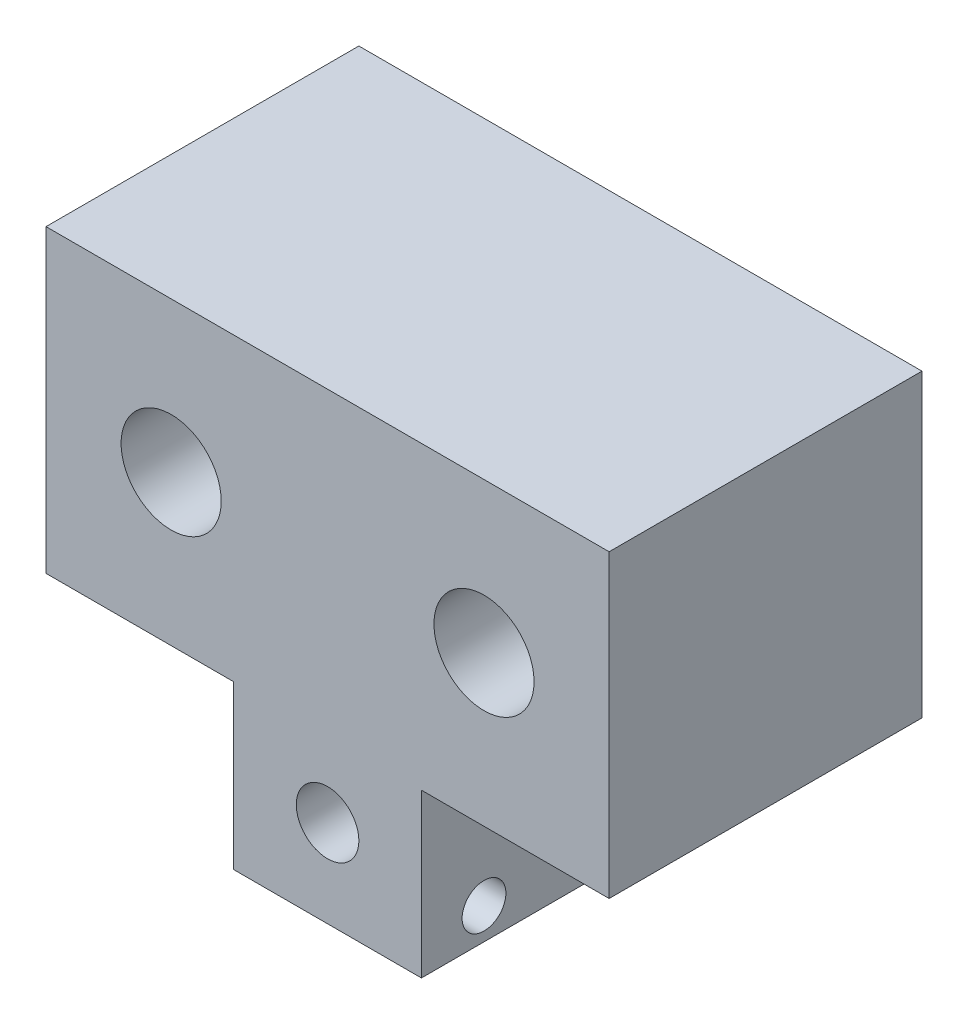
SolidWorks part; units mm, degrees
ref_plane "Plan de face" through (0, 0, 0) normal (0, 0, 1) x (1, 0, 0)
ref_plane "Plan de dessus" through (0, 0, 0) normal (0, 1, 0) x (1, 0, 0)
ref_plane "Plan de droite" through (0, 0, 0) normal (1, 0, 0) x (0, 0, -1)
sketch "Esquisse1" plane through (0, 0, 0) normal (0, 0, 1) x (1, 0, 0)
  line L1 (-18.3024, 11.783) -> (26.6976, 11.783)
  line L2 (-18.3024, 11.783) -> (-18.3024, -12.217)
  line L3 (-18.3024, -12.217) -> (26.6976, -12.217)
  line L4 (26.6976, 11.783) -> (26.6976, -12.217)
  circle A0 centre (-8.3024, -0.217) radius 4
  circle A1 centre (16.6976, -0.217) radius 4
  dimension "D3" = 8
  dimension "D4" = 8
  dimension "D5" = 12
  dimension "D6" = 10
  dimension "D7" = 12
  dimension "D8" = 12
  dimension "D9" = 10
  dimension "D1" = 45
  dimension "D2" = 24
extrude "Boss.-Extru.1" add sketch "Esquisse1" along normal blind 25
sketch "Esquisse2" plane through (0, 0, 25) normal (0, 0, 1) x (1, 0, 0)
  line L0 (-18.3024, -12.217) -> (26.6976, -12.217) construction
  line L1 (-3.3024, -25.217) -> (11.6976, -25.217)
  line L2 (-3.3024, -25.217) -> (-3.3024, -12.217)
  line L3 (-3.3024, -12.217) -> (11.6976, -12.217)
  line L4 (11.6976, -25.217) -> (11.6976, -12.217)
  line L7 (-18.3024, 11.783) -> (-18.3024, -12.217) construction
  circle A0 centre (4.1976, -18.217) radius 2.5
  dimension "D4" = 5
  dimension "D6" = 7.5
  dimension "D1" = 13
  dimension "D2" = 15
  dimension "D3" = 15
  dimension "D5" = 6
extrude "Boss.-Extru.2" add sketch "Esquisse2" against normal blind 20
sketch "Esquisse3" plane through (-3.3024, 0, 0) normal (-1, 0, 0) x (0, 0, 1)
  line L0 (5, -25.217) -> (25, -25.217) construction
  line L1 (25, -12.217) -> (25, -25.217) construction
  circle A0 centre (20, -22.717) radius 1.75
  dimension "D1" = 2.5
  dimension "D2" = 5
extrude "Enlèv. mat.-Extru.1" cut sketch "Esquisse3" against normal blind 20
